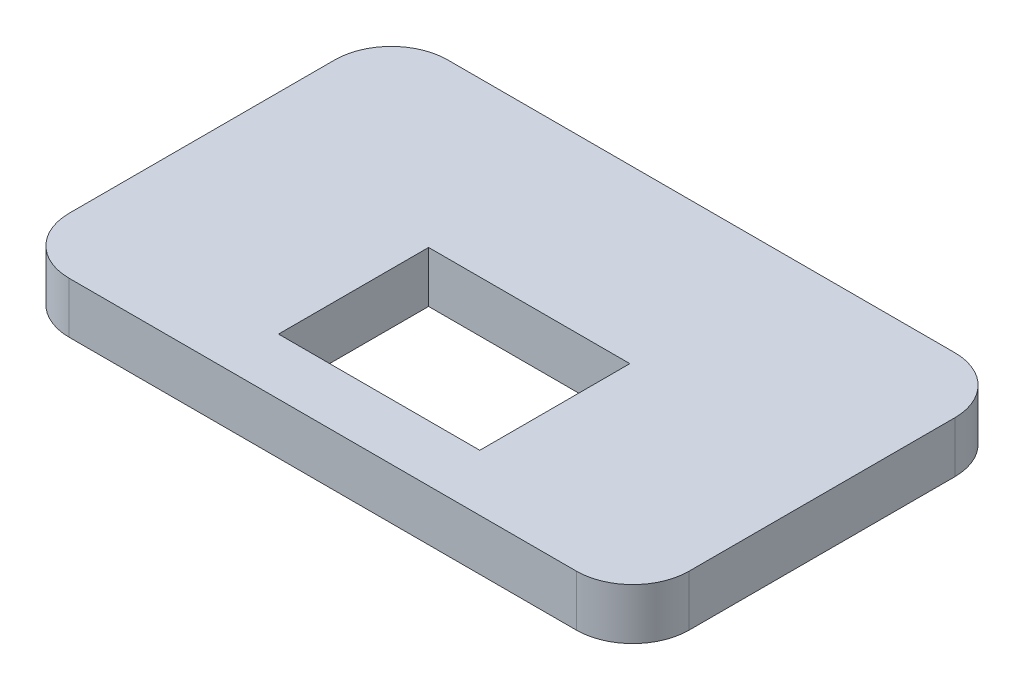
SolidWorks part; units mm, degrees
ref_plane "Front Plane" through (0, 0, 0) normal (0, 0, 1) x (1, 0, 0)
ref_plane "Top Plane" through (0, 0, 0) normal (0, 1, 0) x (1, 0, 0)
ref_plane "Right Plane" through (0, 0, 0) normal (1, 0, 0) x (0, 0, -1)
sketch "Sketch1" plane through (0, 0, 0) normal (0, 1, 0) x (1, 0, 0)
  line L1 (7, 0) -> (70, 0)
  line L2 (0, 7) -> (0, 40)
  line L3 (7, 47) -> (70, 47)
  line L4 (77, 7) -> (77, 40)
  arc A0 (7, 0) -> (0, 7) centre (7, 7) cw
  arc A1 (70, 0) -> (77, 7) centre (70, 7) ccw
  arc A2 (70, 47) -> (77, 40) centre (70, 40) cw
  arc A3 (0, 40) -> (7, 47) centre (7, 40) cw
  point P7 (0, 0)
  point P10 (77, 0)
  point P13 (77, 47)
  point P16 (0, 47)
  dimension "D3" = 7
  dimension "D1" = 77
  dimension "D2" = 47
extrude "Boss-Extrude1" add sketch "Sketch1" along normal blind 6.35
sketch "Sketch2" plane through (0, 6.35, 0) normal (0, 1, 0) x (1, 0, 0)
  line L0 (38.5, 47) -> (38.5, 0) construction
  line L1 (70, 47) -> (7, 47) construction
  line L2 (7, 0) -> (70, 0) construction
  line L3 (38.5, 25.64) -> (38.5, 7) construction
  line L4 (26, 25.64) -> (51, 25.64)
  line L5 (26, 25.64) -> (26, 7)
  line L6 (26, 7) -> (51, 7)
  line L7 (51, 25.64) -> (51, 7)
  dimension "D1" = 25
  dimension "D2" = 18.64
  dimension "D3" = 7
extrude "Cut-Extrude1" cut sketch "Sketch2" against normal through all
